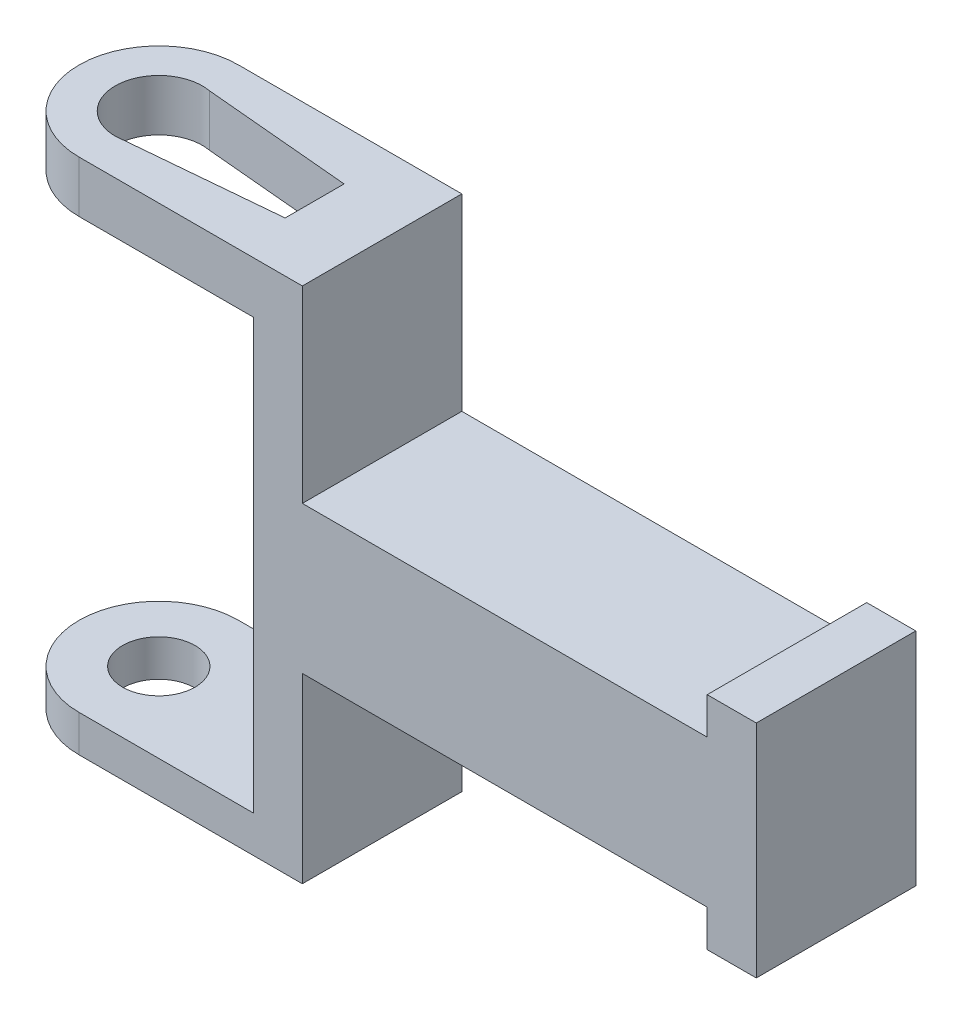
SolidWorks part; units mm, degrees
material "ABS"
ref_plane "Front Plane" through (0, 0, 0) normal (0, 0, 1) x (1, 0, 0)
ref_plane "Top Plane" through (0, 0, 0) normal (0, 1, 0) x (1, 0, 0)
ref_plane "Right Plane" through (0, 0, 0) normal (1, 0, 0) x (0, 0, -1)
sketch "Sketch1" plane through (0, 0, 0) normal (1, 0, 0) x (0, 0, -1)
  line L1 (-6.5, 47.15) -> (6.5, 47.15)
  line L2 (-6.5, 47.15) -> (-6.5, 89.35)
  line L3 (-6.5, 89.35) -> (6.5, 89.35)
  line L4 (6.5, 47.15) -> (6.5, 89.35)
extrude "Boss-Extrude1" add sketch "Sketch1" along normal mid plane 4 from offset 3
sketch "Sketch2" plane through (0, 0, 0) normal (0, 1, 0) x (1, 0, 0)
  circle A0 centre (-19.2, 0) radius 6.5
extrude "Boss-Extrude2" add sketch "Sketch2" along normal mid plane 4.2 from offset 87.25
sketch "Sketch3" plane through (0, 0, 0) normal (0, 1, 0) x (1, 0, 0)
  line L1 (-19.2, -6.5) -> (-1, -6.5)
  line L2 (-19.2, -6.5) -> (-19.2, 6.5)
  line L3 (-19.2, 6.5) -> (-1, 6.5)
  line L4 (-1, -6.5) -> (-1, 6.5)
  circle A0 centre (-19.2, 0) radius 6.5 construction
extrude "Boss-Extrude3" add sketch "Sketch3" along normal mid plane 4.2 from offset 87.25
sketch "Sketch4" plane through (0, 0, 0) normal (0, 1, 0) x (1, 0, 0)
  circle A0 centre (-19.2, 0) radius 3.55
extrude "Cut-Extrude1" cut sketch "Sketch4" against normal mid plane 4.2 from offset 87.25
sketch "Sketch5" plane through (0, 0, 0) normal (0, 1, 0) x (1, 0, 0)
  line L0 (-19.2, -3.55) -> (-6.5, -2.4033)
  line L1 (-6.5, -2.4033) -> (-6.5, 2.4033)
  line L2 (-6.5, 2.4033) -> (-19.2, 3.55)
  line L3 (-19.2, 3.55) -> (-19.2, -3.55)
  circle A0 centre (-19.2, 0) radius 3.55 construction
extrude "Cut-Extrude2" cut sketch "Sketch5" against normal mid plane 4.2 from offset 87.25
sketch "Sketch6" plane through (0, 0, 0) normal (0, 1, 0) x (1, 0, 0)
  circle A0 centre (-19.2, 0) radius 6.5
extrude "Boss-Extrude4" add sketch "Sketch6" along normal mid plane 3 from offset 48.65
sketch "Sketch7" plane through (0, 0, 0) normal (0, 1, 0) x (1, 0, 0)
  line L1 (-19.2, -6.5) -> (-1, -6.5)
  line L2 (-19.2, -6.5) -> (-19.2, 6.5)
  line L3 (-19.2, 6.5) -> (-1, 6.5)
  line L4 (-1, -6.5) -> (-1, 6.5)
extrude "Boss-Extrude5" add sketch "Sketch7" along normal mid plane 3 from offset 48.65
sketch "Sketch8" plane through (0, 0, 0) normal (0, 1, 0) x (1, 0, 0)
  circle A0 centre (-19.2, 0) radius 2.95
extrude "Cut-Extrude3" cut sketch "Sketch8" against normal mid plane 3 from offset 48.65
sketch "Sketch9" plane through (0, 0, 0) normal (1, 0, 0) x (0, 0, -1)
  line L0 (-6.5, 89.35) -> (-6.5, 47.15) construction
  line L1 (-6.5, 62) -> (6.5, 62)
  line L2 (-6.5, 62) -> (-6.5, 74)
  line L3 (-6.5, 74) -> (6.5, 74)
  line L4 (6.5, 62) -> (6.5, 74)
  line L5 (6.5, 47.15) -> (6.5, 89.35) construction
extrude "Boss-Extrude6" add sketch "Sketch9" along normal mid plane 38 from offset 17
sketch "Sketch10" plane through (0, 0, 0) normal (1, 0, 0) x (0, 0, -1)
  line L0 (-6.5, 62) -> (-6.5, 47.15) construction
  line L1 (-6.5, 59) -> (6.5, 59)
  line L2 (-6.5, 59) -> (-6.5, 77)
  line L3 (-6.5, 77) -> (6.5, 77)
  line L4 (6.5, 59) -> (6.5, 77)
  line L5 (6.5, 74) -> (6.5, 89.35) construction
extrude "Boss-Extrude7" add sketch "Sketch10" along normal mid plane 4 from offset 34
